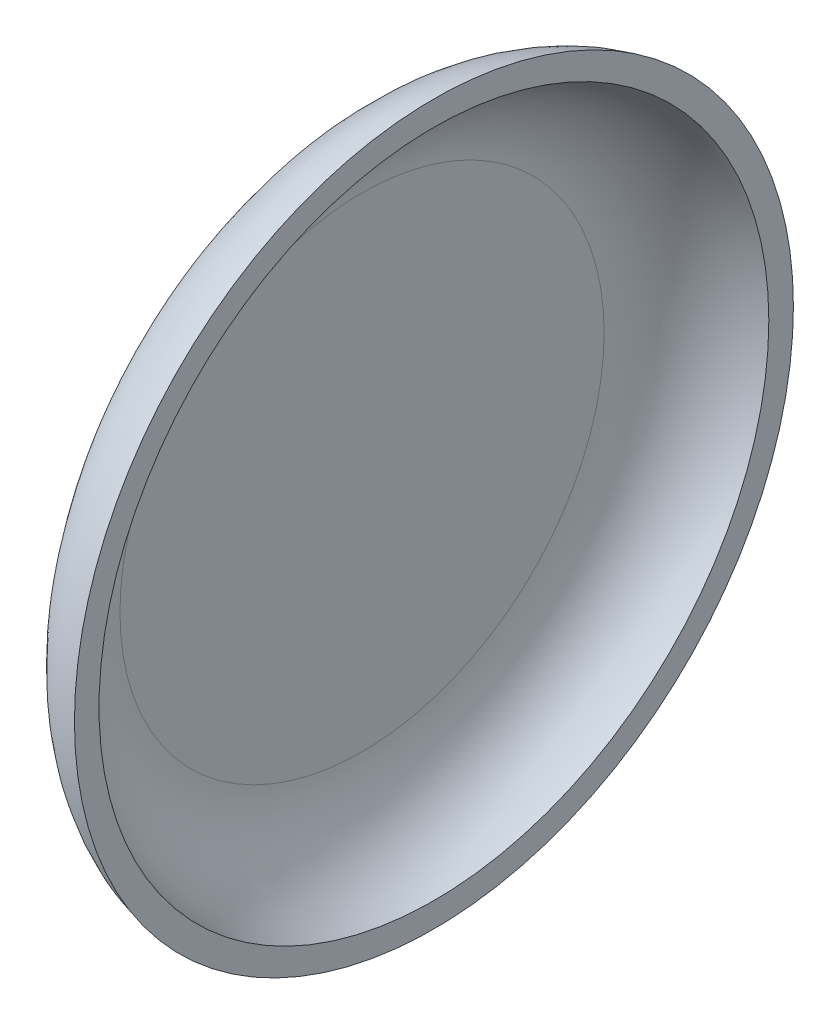
SolidWorks part; units mm, degrees
ref_plane "Front Plane" through (0, 0, 0) normal (0, 0, 1) x (1, 0, 0)
ref_plane "Top Plane" through (0, 0, 0) normal (0, 1, 0) x (1, 0, 0)
ref_plane "Right Plane" through (0, 0, 0) normal (1, 0, 0) x (0, 0, -1)
sketch "Sketch1" plane through (0, 0, 0) normal (0, 0, 1) x (1, 0, 0)
  line L0 (0, 15) -> (0, 0) construction
  line L1 (0, 0) -> (-14.9508, 0) construction
  line L2 (-4, 0) -> (-4, 10.101)
  line L3 (-3, 0) -> (-3, 10.101)
  line L4 (-4, 0) -> (-3, 0)
  line L5 (0, 15) -> (0, 13.974)
  arc A0 (-4, 10.101) -> (0, 15) centre (1, 10.101) cw
  arc A1 (-3, 10.101) -> (0, 13.974) centre (1, 10.101) cw
  arc A2 (-3, 10.101) -> (0.2, 14.0202) centre (1, 10.101) cw construction
  dimension "D2" = 5
  dimension "D1" = 15
  dimension "D3" = 4
  dimension "D4" = 1
revolve "Revolve1" add sketch "Sketch1" angle 360 about L1
